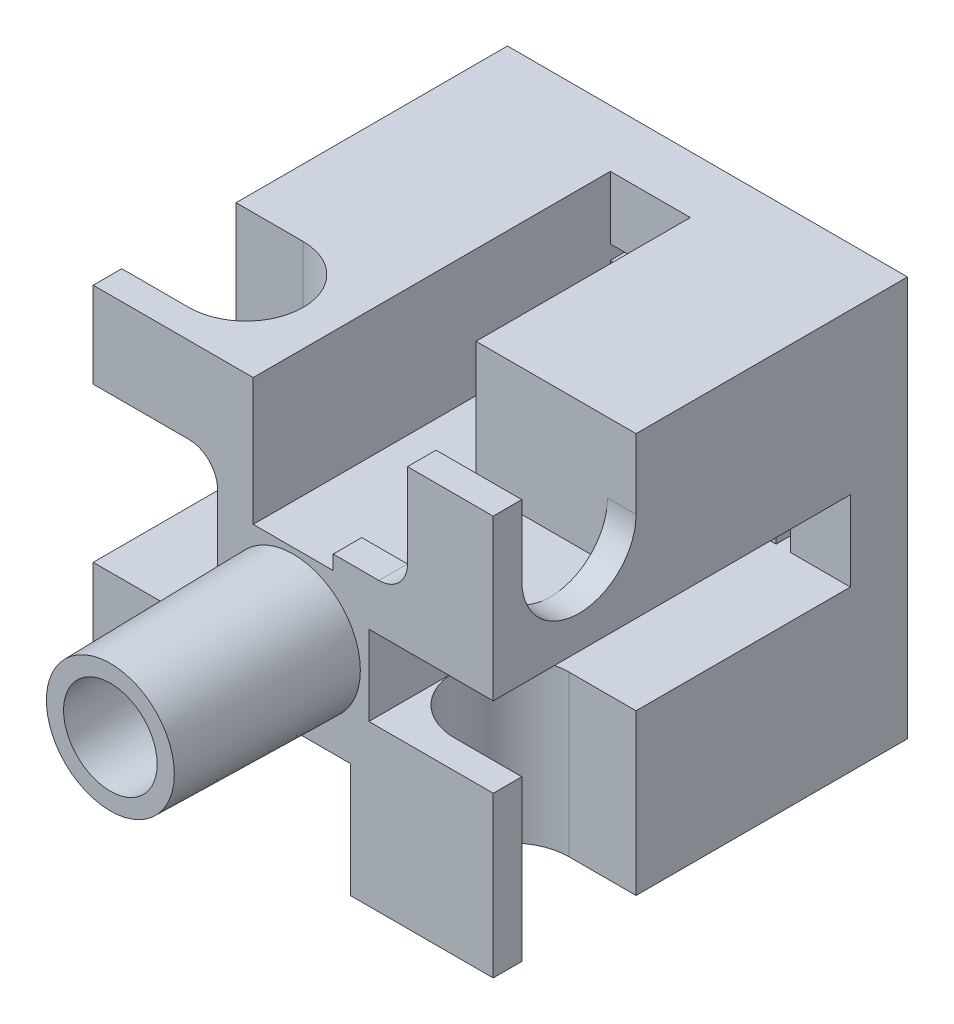
SolidWorks part; units mm, degrees
material "ABS"
ref_plane "Front Plane" through (0, 0, 0) normal (0, 0, 1) x (1, 0, 0)
ref_plane "Top Plane" through (0, 0, 0) normal (0, 1, 0) x (1, 0, 0)
ref_plane "Right Plane" through (0, 0, 0) normal (1, 0, 0) x (0, 0, -1)
sketch "BaseS" plane through (0, 0, 0) normal (0, 0, 1) x (1, 0, 0)
  line L1 (-7, 7) -> (7, 7)
  line L2 (-7, 7) -> (-7, -7)
  line L3 (-7, -7) -> (7, -7)
  line L4 (7, 7) -> (7, -7)
  line L5 (-7, 7) -> (7, -7) construction
  line L6 (-7, -7) -> (7, 7) construction
  point P0 (0, 0)
  dimension "Width" = 14
  dimension "Height" = 14
extrude "BASE" add sketch "BaseS" along normal blind 14.5
sketch "NeutralS" plane through (0, 0, 0) normal (0, 0, -1) x (-1, 0, 0)
  line L0 (0, 0) -> (4.65, 0) construction
  line L1 (4.4, 1.4) -> (4.9, 1.4)
  line L2 (4.4, 1.4) -> (4.4, -1.4)
  line L3 (4.4, -1.4) -> (4.9, -1.4)
  line L4 (4.9, 1.4) -> (4.9, -1.4)
  line L5 (4.4, 1.4) -> (4.9, -1.4) construction
  line L6 (4.4, -1.4) -> (4.9, 1.4) construction
  line L7 (0, 0) -> (0, 7) construction
  line L8 (-7, 7) -> (7, 7) construction
  point P0 (4.65, 0)
  dimension "D1" = 9.3
  dimension "Height" = 2.8
  dimension "Width" = 0.5
extrude "NEUTRAL" cut sketch "NeutralS" against normal through all
mirror "LINE HM" about plane through (0, 0, 0) normal (1, 0, 0) of "NEUTRAL"
sketch "GroundS" plane through (0, 0, 0) normal (0, 0, -1) x (-1, 0, 0)
  line L0 (0, 4.55) -> (0, 0) construction
  line L1 (-1.4, 4.8) -> (1.4, 4.8)
  line L2 (-1.4, 4.8) -> (-1.4, 4.3)
  line L3 (-1.4, 4.3) -> (1.4, 4.3)
  line L4 (1.4, 4.8) -> (1.4, 4.3)
  line L5 (-1.4, 4.8) -> (1.4, 4.3) construction
  line L6 (-1.4, 4.3) -> (1.4, 4.8) construction
  line L7 (-4.4, 0) -> (0, 0) construction
  line L8 (-4.4, 1.4) -> (-4.4, -1.4) construction
  line L9 (-4.4, -1.4) -> (-4.9, -1.4) construction
  point P0 (0, 4.55)
  dimension "D1" = 4.55
  dimension "Width" = 2.8
  dimension "D2" = 6.2
  dimension "Height" = 0.5
extrude "GROUND" cut sketch "GroundS" against normal through all
sketch "Sketch1" plane through (0, 7, 0) normal (0, 1, 0) x (1, 0, 0)
  line L0 (1.4, 0) -> (-1.4, 0) construction
  line L1 (-1.4, -2) -> (1.4, -2)
  line L2 (-1.4, -2) -> (-1.4, -13.5)
  line L3 (-1.4, -13.5) -> (1.4, -13.5)
  line L4 (1.4, -2) -> (1.4, -13.5)
  line L6 (-1.4, -14.5) -> (-1.4, 0) construction
  line L7 (7, 0) -> (-7, 0) construction
  line L9 (7, -14.5) -> (-7, -14.5) construction
  point P4 (1.4, -14.5)
  point P6 (0, 0)
  point P13 (0, 0)
  point P14 (0, 0)
  point P15 (1.4, -14.7058)
  point P18 (1.4, -13.1706)
  dimension "D1" = 2
  dimension "D2" = 1
extrude "TOP GROUND AREA" cut sketch "Sketch1" against normal up to next
sketch "Sketch15" plane through (0, 4.3, 0) normal (0, 1, 0) x (1, 0, 0)
  line L0 (-1.4, -2) -> (1.4, -2) construction
  line L1 (-1.4, -14.5) -> (1.4, -14.5)
  line L2 (-1.4, -14.5) -> (-1.4, -2)
  line L3 (-1.4, -2) -> (1.4, -2)
  line L4 (1.4, -14.5) -> (1.4, -2)
  point P4 (-1.4, -14.5)
  point P6 (1.4, -14.5)
extrude "GND POCKET EXTRA CUT" cut sketch "Sketch15" against normal blind 1.75
sketch "Sketch2" plane through (0, 0, 14.5) normal (0, 0, 1) x (1, 0, 0)
  line L0 (4, 7) -> (4, 4.05)
  line L1 (7, 7) -> (-7, 7) construction
  line L2 (3, 3.05) -> (0.6, 3.05)
  line L3 (0.6, 3.05) -> (0.6, 2.55)
  line L4 (-1.4, 2.55) -> (-1.4, 4.8) construction
  line L5 (-1.4, 7) -> (-1.4, 2.55)
  line L6 (-1.4, 2.55) -> (0.6, 2.55)
  line L7 (-1.4, 7) -> (4, 7)
  line L8 (-1.4, 2.55) -> (1.4, 2.55) construction
  line L10 (7, -7) -> (7, 7) construction
  arc A0 (3, 3.05) -> (4, 4.05) centre (3, 4.05) ccw
  point P4 (0, 0)
  point P6 (0.3554, 3.75)
  point P7 (0.6, 3.2464)
  point P11 (0.6, 4)
  point P12 (-1.4, 3.75)
  point P13 (0, 0)
  point P14 (0, 0)
  point P15 (0.4777, 4.25)
  point P17 (-1.38, 3.75)
  point P20 (0.5919, 3.75)
  point P21 (-1.4, 3.75)
  point P22 (4, 4.837)
  point P23 (-1.4, 7)
  point P24 (-1.4, 7)
  point P27 (4, 3.05)
  point P28 (0.6, 4.6918)
  point P29 (0, 0)
  point P30 (0.6978, 4.982)
  dimension "D4" = 1
  dimension "D1" = 2
  dimension "D2" = 3
  dimension "D3" = 0.5
extrude "SIDE GROUND AREA" cut sketch "Sketch2" against normal blind 5
sketch "Sketch3" plane through (7, 0, 0) normal (1, 0, 0) x (0, 0, -1)
  line L0 (-11.5, 9.45) -> (-11.5, 4.55) construction
  line L1 (-14.5, 7) -> (0, 7) construction
  line L2 (-9.5, 9.45) -> (-9.5, 4.55)
  line L3 (-13.5, 9.45) -> (-13.5, 4.55)
  line L4 (-14.5, -7) -> (-14.5, 7) construction
  line L6 (-9.5, 7) -> (-9.5, 3.05) construction
  line L10 (-14.5, 2.55) -> (-2, 2.55) construction
  arc A0 (-9.5, 9.45) -> (-13.5, 9.45) centre (-11.5, 9.45) ccw
  arc A1 (-13.5, 4.55) -> (-9.5, 4.55) centre (-11.5, 4.55) ccw
  point P4 (-11.5, 7)
  point P13 (-13.5, 5.0941)
  point P15 (0, 0)
  dimension "D1" = 1
extrude "SIDE GND TERMINAL SCREW AREA" cut sketch "Sketch3" against normal up to surface (5.6 mm away) up to face at (1.4, 4.34, 5.6)
sketch "Sketch4" plane through (0, 4.3, 0) normal (0, 1, 0) x (1, 0, 0)
  line L0 (-1.4, -2) -> (-1.4, 0) construction
  line L1 (-1.4, -9.5) -> (6, -9.5)
  line L2 (-1.4, -9.5) -> (-1.4, -13.5)
  line L3 (-1.4, -13.5) -> (6, -13.5)
  line L4 (6, -9.5) -> (6, -13.5)
  line L6 (7, -13.5) -> (7, -9.5) construction
  line L7 (7, -9.5) -> (1.4, -9.5) construction
  line L8 (7, -13.5) -> (4, -13.5) construction
  point P6 (-1.4, -9.6299)
  point P7 (3.6781, -9.4313)
  point P9 (0, 0)
  point P11 (0, 0)
  point P12 (0, 0)
  point P13 (0, 0)
  point P14 (0, 0)
  point P18 (0, 0)
  point P19 (4, -9.6298)
  point P20 (6.2005, -9.6148)
  dimension "D1" = 1
extrude "POCKET GND TERMINAL AREA" cut sketch "Sketch4" along normal up to next and the other way up to surface
sketch "Sketch6" plane through (-7, 0, 0) normal (-1, 0, 0) x (0, 0, 1)
  line L1 (2, -1.4) -> (14.5, -1.4)
  line L2 (2, -1.4) -> (2, 2.2)
  line L3 (2, 2.2) -> (14.5, 2.2)
  line L4 (14.5, -1.4) -> (14.5, 2.2)
  line L6 (0, 7) -> (0, -7) construction
  line L9 (14.5, -1.4) -> (0, -1.4) construction
  line L10 (14.5, 7) -> (14.5, -7) construction
  point P4 (14.5, -1.3406)
  point P6 (9.5, -1.5)
  point P7 (9.5, -1.1345)
  point P11 (0, 0)
  point P12 (0, 0)
  point P13 (0, 0)
  dimension "D1" = 2
  dimension "D2" = 3.6
extrude "NEUTRAL SIDE AREA CUT" cut sketch "Sketch6" against normal offset from surface (4.35 mm away) 1.75 up to face at (-4.4, 0, 7.25) offset beyond the face yes
sketch "Sketch5" plane through (0, 7, 0) normal (0, 1, 0) x (1, 0, 0)
  line L0 (-9.35, -11.5) -> (-4.65, -11.5) construction
  line L1 (-9.35, -9.5) -> (-4.65, -9.5)
  line L2 (-9.35, -13.5) -> (-4.65, -13.5)
  line L3 (-1.4, -14.5) -> (-7, -14.5) construction
  line L4 (-7, -14.5) -> (-7, 0) construction
  line L5 (-2.65, -14.5) -> (-2.65, -2) construction
  arc A0 (-9.35, -9.5) -> (-9.35, -13.5) centre (-9.35, -11.5) ccw
  arc A1 (-4.65, -13.5) -> (-4.65, -9.5) centre (-4.65, -11.5) ccw
  point P2 (-7, -11.5)
  point P9 (-2.65, -11.5)
  point P10 (0, 0)
  point P13 (-7, -11.5)
  point P16 (0, 0)
  dimension "D1" = 1
  dimension "D2" = 4
extrude "NEUTRAL SIDE SCREW TERMINAL" cut sketch "Sketch5" against normal up to surface (8.4 mm away) up to face at (-4.7375, -1.4, 4.625)
sketch "Sketch7" plane through (0, 0, 14.5) normal (0, 0, 1) x (1, 0, 0)
  line L0 (-7, 2.2) -> (-2.65, 2.2)
  line L1 (-2.65, 2.2) -> (-2.65, 3)
  line L2 (-3.65, 4) -> (-7, 4)
  line L4 (-7, 4) -> (-7, 2.2)
  line L5 (-1.4, 7) -> (-7, 7) construction
  arc A0 (-3.65, 4) -> (-2.65, 3) centre (-3.65, 3) cw
  point P4 (0, 0)
  point P7 (0, 0)
  point P12 (0, 0)
  point P13 (-3.9, 2.1)
  dimension "D2" = 1
  dimension "D1" = 3
extrude "NEUTRAL SIDE CURVED WALL CUT" cut sketch "Sketch7" against normal up to next
sketch "Sketch8" plane through (7, 0, 0) normal (1, 0, 0) x (0, 0, -1)
  line L0 (-14.5, -7) -> (-14.5, 7) construction
  line L1 (-14.5, 1.4) -> (-2, 1.4)
  line L2 (-14.5, 1.4) -> (-14.5, -1.4)
  line L3 (-14.5, -1.4) -> (-2, -1.4)
  line L4 (-2, 1.4) -> (-2, -1.4)
  line L6 (-14.5, 1.4) -> (0, 1.4) construction
  line L7 (-14.5, -1.4) -> (0, -1.4) construction
  line L8 (0, -7) -> (0, 7) construction
  point P6 (-0.4774, -1.4)
  point P12 (0, 0)
  point P13 (0, 0)
  dimension "D1" = 2
extrude "LINE AREA CUT" cut sketch "Sketch8" against normal offset from surface (4.35 mm away) 1.75 up to face at (4.4, 0, 7.25) offset beyond the face yes
sketch "Sketch9" plane through (0, -7, 0) normal (0, -1, 0) x (-1, 0, 0)
  line L0 (-4.65, -11.5) -> (-7, -11.5) construction
  line L1 (-4.65, -13.5) -> (-7, -13.5)
  line L2 (-4.65, -9.5) -> (-7, -9.5)
  line L3 (-7, -9.5) -> (-1.4, -9.5) construction
  line L4 (-7, -13.5) -> (-4, -13.5) construction
  line L6 (-2.65, -2) -> (-2.65, -14.5) construction
  line L7 (-7, -14.5) -> (-7, 0) construction
  arc A0 (-4.65, -13.5) -> (-4.65, -9.5) centre (-4.65, -11.5) ccw
  arc A1 (-7, -9.5) -> (-7, -13.5) centre (-7, -11.5) ccw
  point P2 (-5.825, -11.5)
  point P13 (-7, -9.5)
extrude "LINE SIDE SCREW TERMINAL" cut sketch "Sketch9" against normal up to surface (5.6 mm away)
sketch "Sketch10" plane through (0, -7, 0) normal (0, -1, 0) x (1, 0, 0)
  line L0 (-7, 14.5) -> (-7, 0) construction
  line L1 (-5, 14.5) -> (2, 14.5)
  line L2 (-5, 14.5) -> (-5, 2.2)
  line L3 (-5, 2.2) -> (2, 2.2)
  line L4 (2, 14.5) -> (2, 2.2)
  line L5 (-7, 14.5) -> (7, 14.5) construction
  line L6 (-7, 0) -> (7, 0) construction
  point P4 (-0.8034, 2.8325)
  point P7 (-0.9504, 14.5)
  dimension "D1" = 2
  dimension "D2" = 2.2
  dimension "D3" = 7
extrude "BOTTOM POCKET" cut sketch "Sketch10" against normal blind 4
sketch "Sketch11" plane through (0, 0, 0) normal (0, 0, -1) x (-1, 0, 0)
  circle A0 centre (0, 0) radius 2.5
  dimension "D1" = 5
extrude "FASTENER TOP BORE" cut sketch "Sketch11" against normal blind 0.5
sketch "Sketch13" plane through (0, 0, 14.5) normal (0, 0, 1) x (1, 0, 0)
  circle A0 centre (0, 0) radius 2.35
  dimension "D1" = 4.7
extrude "FASTENER BOSS" add sketch "Sketch13" along normal blind 6.4 draft 1
sketch "Sketch12" plane through (0, 0, 0.5) normal (0, 0, -1) x (-1, 0, 0)
  circle A0 centre (0, 0) radius 2
  circle A1 centre (0, 0) radius 2.5 construction
  dimension "D1" = 0.5
  dimension "RefDia" = 4
sketch "Sketch14" plane through (0, 0, 20.9) normal (0, 0, 1) x (1, 0, 0)
  circle A0 centre (0, 0) radius 1.6383
  circle A1 centre (0, 0) radius 2.2383 construction
  point P2 (0, 0)
  dimension "D1" = 0.6
loft "FASTENER CLEARANCE HOLE" cut profiles "Sketch12", "Sketch14"
